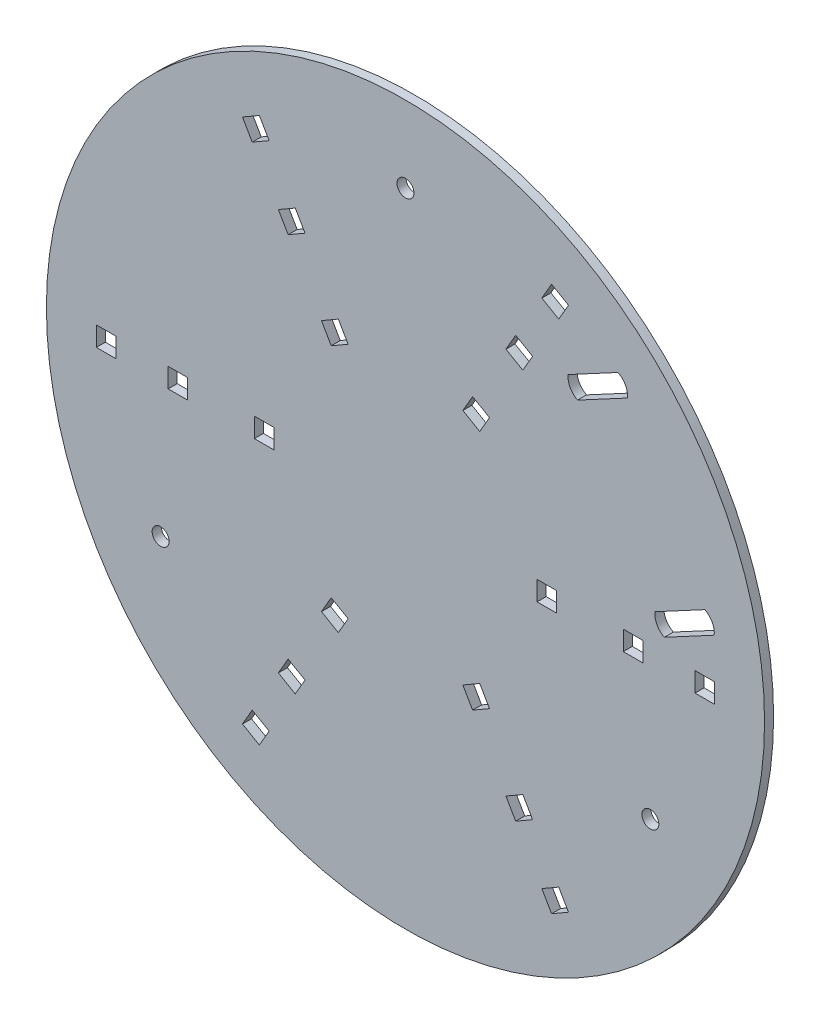
SolidWorks part; units mm, degrees
ref_plane "Front Plane" through (0, 0, 0) normal (0, 0, 1) x (1, 0, 0)
ref_plane "Top Plane" through (0, 0, 0) normal (0, 1, 0) x (1, 0, 0)
ref_plane "Right Plane" through (0, 0, 0) normal (1, 0, 0) x (0, 0, -1)
sketch "Sketch1" plane through (0, 0, 0) normal (0, 0, 1) x (1, 0, 0)
  circle A0 centre (0, 0) radius 63.5
  dimension "D1" = 127
extrude "Boss-Extrude1" add sketch "Sketch1" along normal blind 1.6
sketch "Sketch2" plane through (0, 0, 0) normal (0, 0, -1) x (-1, 0, 0)
  circle A0 centre (0, 0) radius 50
  circle A1 centre (0, 50) radius 1.5
  circle A2 centre (43.3013, -25) radius 1.5
  circle A3 centre (-43.3013, -25) radius 1.5
  point P11 (0, 0)
  dimension "D1" = 100
  dimension "D2" = 3
  dimension "D3" = 3
sketch "Sketch3" plane through (0, 0, 0) normal (0, 0, -1) x (-1, 0, 0)
  circle A0 centre (-34.0063, 36.6548) radius 1.75
  circle A1 centre (-49.3547, 8.0073) radius 1.75
  circle A2 centre (0, 0) radius 63.5 construction
  dimension "D1" = 3.5
  dimension "D2" = 3.5
  dimension "D3" = 32.5
  dimension "D4" = 50
  dimension "D5" = 50
extrude "Cut-Extrude4" cut sketch "Sketch3" against normal blind 1.6
extrude "Cut-Extrude5" cut sketch "Sketch2" against normal blind 1.6 contours A1 | A3 | A2
sketch "Sketch4" plane through (0, 0, 0) normal (0, 0, -1) x (-1, 0, 0)
  line L0 (-34.8328, 35.1122) -> (-48.5282, 9.5498) construction
  line L2 (-52.9355, 11.9111) -> (-44.1209, 7.1886)
  line L3 (-54.5884, 8.826) -> (-45.7738, 4.1034)
  line L6 (-39.2401, 37.4735) -> (-30.4255, 32.7509)
  line L7 (-37.5872, 40.5586) -> (-28.7726, 35.836)
  arc A1 (-45.7738, 4.1034) -> (-44.1209, 7.1886) centre (-47.151, 6.8266) ccw
  circle A2 centre (-34.0063, 36.6548) radius 1.75 construction
  arc A3 (-30.4255, 32.7509) -> (-28.7726, 35.836) centre (-31.8027, 35.4741) ccw
  arc A4 (-39.2401, 37.4735) -> (-37.5872, 40.5586) centre (-36.21, 37.8354) cw
  arc A5 (-54.5884, 8.826) -> (-52.9355, 11.9111) centre (-51.5583, 9.1879) cw
  dimension "D3" = 5
extrude "Cut-Extrude6" cut sketch "Sketch4" against normal blind 10 contours L2 A1 L3 A5 | L6 A3 L7 A4
sketch "Sketch5" plane through (0, 0, 0) normal (0, 0, -1) x (-1, 0, 0)
  line L0 (0, 0) -> (-43.3013, -25) construction
  line L1 (-43.3013, -25) -> (0, -25) construction
  line L2 (0, -25) -> (0, 0) construction
  line L3 (0, 0) -> (-52.94, 0) construction
  line L4 (-14.8564, 22.282) -> (-11.8686, 24.007)
  line L5 (-23.275, -1.725) -> (-26.725, -1.725)
  line L6 (-23.275, -1.725) -> (-23.275, 1.725)
  line L7 (-23.275, 1.725) -> (-26.725, 1.725)
  line L8 (-26.725, -1.725) -> (-26.725, 1.725)
  line L9 (-23.275, -1.725) -> (-26.725, 1.725) construction
  line L10 (-23.275, 1.725) -> (-26.725, -1.725) construction
  line L11 (-38.515, -1.725) -> (-41.965, -1.725)
  line L12 (-38.515, -1.725) -> (-38.515, 1.725)
  line L13 (-38.515, 1.725) -> (-41.965, 1.725)
  line L14 (-41.965, -1.725) -> (-41.965, 1.725)
  line L15 (-38.515, -1.725) -> (-41.965, 1.725) construction
  line L16 (-38.515, 1.725) -> (-41.965, -1.725) construction
  line L17 (-51.215, -1.725) -> (-54.665, -1.725)
  line L18 (-51.215, -1.725) -> (-51.215, 1.725)
  line L19 (-51.215, 1.725) -> (-54.665, 1.725)
  line L20 (-54.665, -1.725) -> (-54.665, 1.725)
  line L21 (-51.215, -1.725) -> (-54.665, 1.725) construction
  line L22 (-51.215, 1.725) -> (-54.665, -1.725) construction
  line L23 (-10.1436, 21.0192) -> (-11.8686, 24.007)
  line L24 (-13.1314, 19.2942) -> (-14.8564, 22.282)
  line L25 (-13.1314, 19.2942) -> (-10.1436, 21.0192)
  line L26 (-22.4764, 35.4803) -> (-19.4886, 37.2053)
  line L27 (-17.7636, 34.2175) -> (-19.4886, 37.2053)
  line L28 (-20.7514, 32.4925) -> (-17.7636, 34.2175)
  line L29 (-20.7514, 32.4925) -> (-22.4764, 35.4803)
  line L30 (-28.8264, 46.4788) -> (-25.8386, 48.2038)
  line L31 (-27.1014, 43.491) -> (-28.8264, 46.4788)
  line L32 (-24.1136, 45.216) -> (-25.8386, 48.2038)
  line L33 (-27.1014, 43.491) -> (-24.1136, 45.216)
  line L34 (11.8686, 24.007) -> (14.8564, 22.282)
  line L35 (13.1314, 19.2942) -> (14.8564, 22.282)
  line L36 (10.1436, 21.0192) -> (11.8686, 24.007)
  line L37 (10.1436, 21.0192) -> (13.1314, 19.2942)
  line L38 (19.4886, 37.2053) -> (22.4764, 35.4803)
  line L39 (20.7514, 32.4925) -> (22.4764, 35.4803)
  line L40 (17.7636, 34.2175) -> (20.7514, 32.4925)
  line L41 (17.7636, 34.2175) -> (19.4886, 37.2053)
  line L42 (25.8386, 48.2038) -> (28.8264, 46.4788)
  line L43 (24.1136, 45.216) -> (25.8386, 48.2038)
  line L44 (27.1014, 43.491) -> (28.8264, 46.4788)
  line L45 (24.1136, 45.216) -> (27.1014, 43.491)
  line L46 (26.725, 1.725) -> (26.725, -1.725)
  line L47 (23.275, -1.725) -> (26.725, -1.725)
  line L48 (23.275, 1.725) -> (26.725, 1.725)
  line L49 (23.275, 1.725) -> (23.275, -1.725)
  line L50 (41.965, 1.725) -> (41.965, -1.725)
  line L51 (38.515, -1.725) -> (41.965, -1.725)
  line L52 (38.515, 1.725) -> (38.515, -1.725)
  line L53 (38.515, 1.725) -> (41.965, 1.725)
  line L54 (54.665, 1.725) -> (54.665, -1.725)
  line L55 (51.215, 1.725) -> (54.665, 1.725)
  line L56 (51.215, -1.725) -> (54.665, -1.725)
  line L57 (51.215, 1.725) -> (51.215, -1.725)
  line L58 (14.8564, -22.282) -> (11.8686, -24.007)
  line L59 (10.1436, -21.0192) -> (11.8686, -24.007)
  line L60 (13.1314, -19.2942) -> (14.8564, -22.282)
  line L61 (13.1314, -19.2942) -> (10.1436, -21.0192)
  line L62 (22.4764, -35.4803) -> (19.4886, -37.2053)
  line L63 (17.7636, -34.2175) -> (19.4886, -37.2053)
  line L64 (20.7514, -32.4925) -> (17.7636, -34.2175)
  line L65 (20.7514, -32.4925) -> (22.4764, -35.4803)
  line L66 (28.8264, -46.4788) -> (25.8386, -48.2038)
  line L67 (27.1014, -43.491) -> (28.8264, -46.4788)
  line L68 (24.1136, -45.216) -> (25.8386, -48.2038)
  line L69 (27.1014, -43.491) -> (24.1136, -45.216)
  line L70 (-11.8686, -24.007) -> (-14.8564, -22.282)
  line L71 (-13.1314, -19.2942) -> (-14.8564, -22.282)
  line L72 (-10.1436, -21.0192) -> (-11.8686, -24.007)
  line L73 (-10.1436, -21.0192) -> (-13.1314, -19.2942)
  line L74 (-19.4886, -37.2053) -> (-22.4764, -35.4803)
  line L75 (-20.7514, -32.4925) -> (-22.4764, -35.4803)
  line L76 (-17.7636, -34.2175) -> (-20.7514, -32.4925)
  line L77 (-17.7636, -34.2175) -> (-19.4886, -37.2053)
  line L78 (-25.8386, -48.2038) -> (-28.8264, -46.4788)
  line L79 (-24.1136, -45.216) -> (-25.8386, -48.2038)
  line L80 (-27.1014, -43.491) -> (-28.8264, -46.4788)
  line L81 (-24.1136, -45.216) -> (-27.1014, -43.491)
  line L82 (0, 0) -> (26.6205, -46.108) construction
  line L83 (26.6205, -46.108) -> (43.3013, -25) construction
  line L84 (43.3013, -25) -> (0, 0) construction
  line L85 (0, 0) -> (27.3325, 47.3413) construction
  line L86 (27.3325, 47.3413) -> (0, 50) construction
  line L87 (0, 50) -> (0, 0) construction
  circle A0 centre (0, 0) radius 11.1146
  circle A1 centre (0, 0) radius 11.1146
  circle A2 centre (0, 0) radius 11.1146
  circle A3 centre (0, 0) radius 11.1146
  circle A4 centre (0, 0) radius 11.1146
  circle A5 centre (0, 0) radius 11.1146
  point P4 (-25, 0)
  point P11 (-40.24, 0)
  point P89 (0, 0)
  dimension "D1" = 12.7
  dimension "D2" = 15.24
  dimension "D3" = 25
  dimension "D4" = 3.45
  dimension "D5" = 3.45
  dimension "D7" = 30
  dimension "D8" = 30
  dimension "D6" = 6
extrude "Cut-Extrude7" cut sketch "Sketch5" against normal blind 10 contours L20 L17 L18 L19 | L79 L81 L80 L78 | L31 L33 L32 L30 | L13 L14 L11 L12 | L7 L8 L5 L6 | L48 L46 L47 L49 | L53 L50 L51 L52 | L55 L54 L56 L57 | L60 L58 L59 L61 | L65 L62 L63 L64 | L68 L66 L67 L69 | L71 L70 L72 L73 | L75 L74 L77 L76 | L27 L26 L29 L28 | L24 L4 L23 L25 | L36 L34 L35 L37 | L41 L38 L39 L40 | L43 L42 L44 L45
